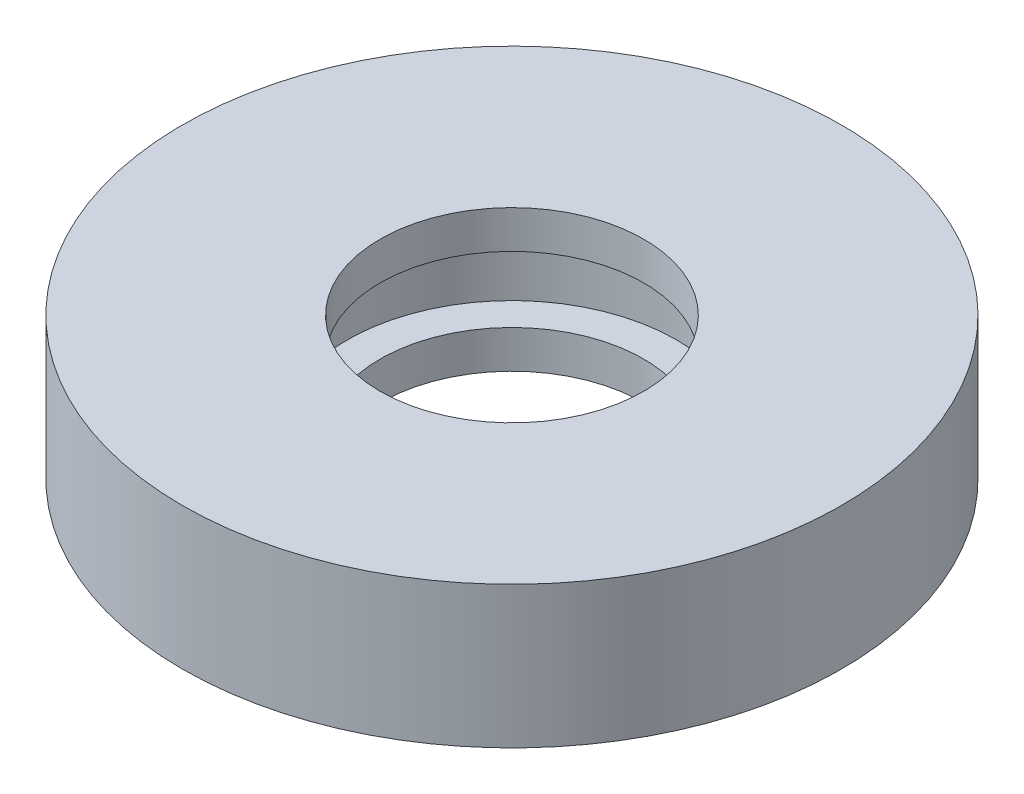
SolidWorks part; units mm, degrees
ref_plane "Front Plane" through (0, 0, 0) normal (0, 0, 1) x (1, 0, 0)
ref_plane "Top Plane" through (0, 0, 0) normal (0, 1, 0) x (1, 0, 0)
ref_plane "Right Plane" through (0, 0, 0) normal (1, 0, 0) x (0, 0, -1)
sketch "Sketch1" plane through (0, 0, 0) normal (1, 0, 0) x (0, 0, -1)
  line L0 (0, 562.013) -> (0, -482.1429) construction
  line L6 (0, 0) -> (-400, 0) construction
  line L10 (-250, 50) -> (-250, -50)
  line L11 (-250, -50) -> (-200, -50)
  line L12 (-200, -50) -> (-200, -107.5)
  line L22 (-250, 50) -> (-200, 50)
  line L24 (-200, 107.5) -> (-200, 50)
  line L25 (-275, -107.5) -> (-275, -82.5)
  line L26 (-275, -82.5) -> (-220, -82.5)
  line L27 (-220, -82.5) -> (-220, -107.5)
  line L41 (-200, 107.5) -> (-500, 107.5)
  line L59 (-275, -107.5) -> (-500, -107.5)
  line L61 (-500, 107.5) -> (-500, -107.5)
  line L62 (-220, -107.5) -> (-200, -107.5)
  point P13 (-200, 0)
  point P16 (-400, 0)
  dimension "D1" = 50
  dimension "D2" = 20
  dimension "D3" = 215
  dimension "D4" = 550
  dimension "D5" = 25
  dimension "D9" = 100
  dimension "D12" = 200
  dimension "D13" = 440
revolve "Revolve1" add sketch "Sketch1" angle 360 about L0
sketch "Sketch2" plane through (0, 0, 0) normal (0, 0, 1) x (1, 0, 0)
  line L0 (-500, 107.5) -> (-500, -107.5) construction
  line L4 (-375, 100) -> (-375, -100) construction
  line L5 (-375, 100) -> (-375, -100)
  line L6 (-375, -100) -> (-375, 100) construction
  arc A0 (-375, -100) -> (-375, 100) centre (-375, 0) cw
  dimension "D1" = 125
  dimension "D2" = 200
revolve "Cut-Revolve1" cut sketch "Sketch2" angle 360 about L5
pattern_circular "CirPattern1" count 6 over 360 about axis through (0, 0, 0) along (0, 1, 0) of "Cut-Revolve1"
